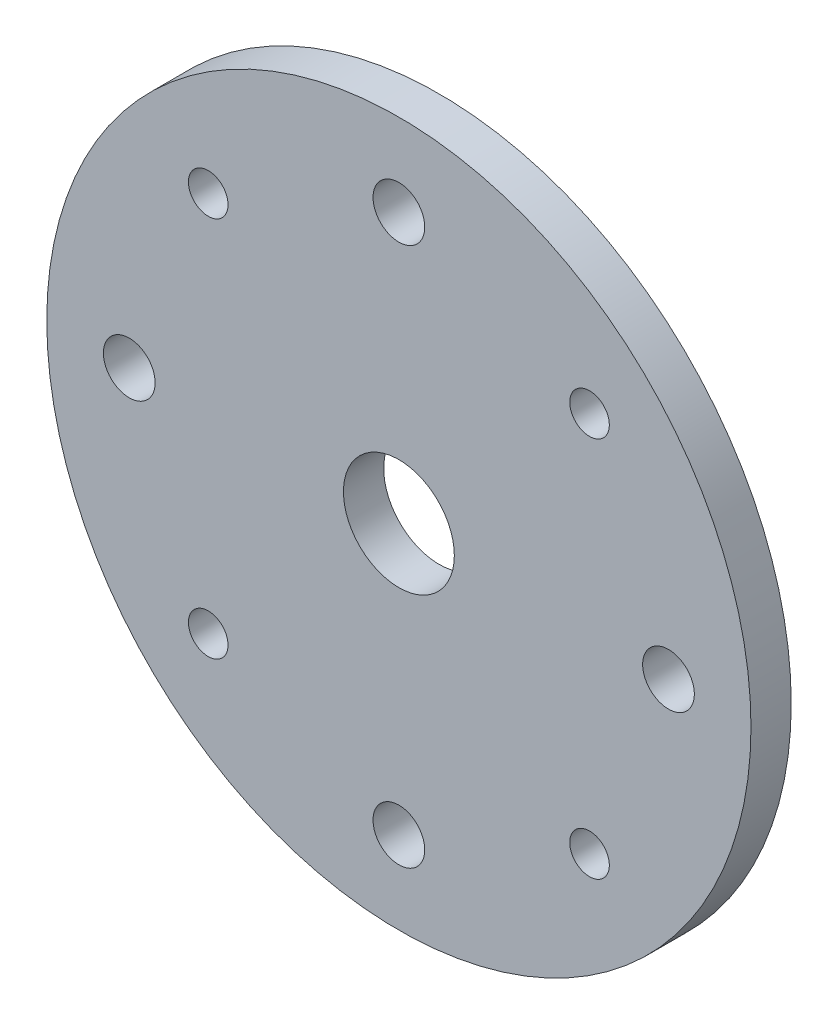
SolidWorks part; units mm, degrees
material "6061-T6 (SS)"
ref_plane "Front" through (0, 0, 0) normal (0, 0, 1) x (1, 0, 0)
ref_plane "Top" through (0, 0, 0) normal (0, 1, 0) x (1, 0, 0)
ref_plane "Right" through (0, 0, 0) normal (1, 0, 0) x (0, 0, -1)
sketch "Sketch1" plane through (0, 0, 0) normal (0, 0, 1) x (1, 0, 0)
  circle A0 centre (0, 0) radius 44.45
  circle A1 centre (0, 0) radius 7
  circle A2 centre (0, 0) radius 34.036 construction
  circle A3 centre (0, 34.036) radius 3.2639
  circle A4 centre (34.036, 0) radius 3.2639
  circle A5 centre (0, -34.036) radius 3.2639
  circle A6 centre (-34.036, 0) radius 3.2639
  circle A8 centre (24.0671, 24.0671) radius 2.5
  circle A10 centre (24.0671, -24.0671) radius 2.5
  circle A12 centre (-24.0671, -24.0671) radius 2.5
  circle A14 centre (-24.0671, 24.0671) radius 2.5
  point P23 (0, 0)
  point P31 (0, 0)
  dimension "D1" = 88.9
  dimension "D2" = 14
  dimension "D3" = 4
  dimension "D4" = 6.5278
  dimension "D5" = 68.072
extrude "Boss-Extrude1" add sketch "Sketch1" along normal blind 5.08
